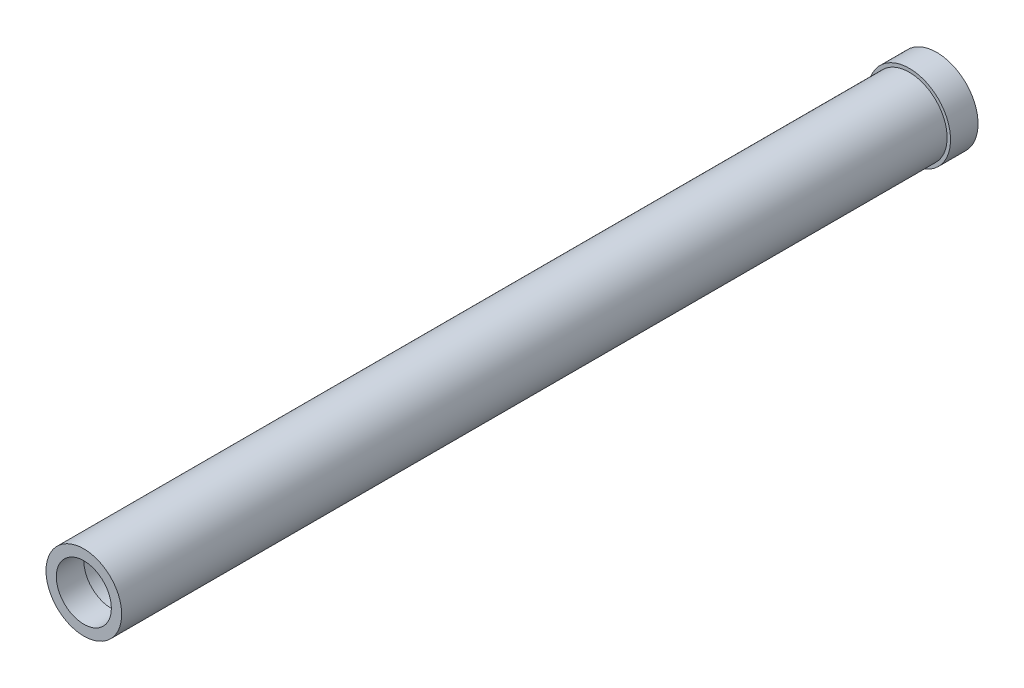
SolidWorks part; units mm, degrees
ref_plane "Front Plane" through (0, 0, 0) normal (0, 0, 1) x (1, 0, 0)
ref_plane "Top Plane" through (0, 0, 0) normal (0, 1, 0) x (1, 0, 0)
ref_plane "Right Plane" through (0, 0, 0) normal (1, 0, 0) x (0, 0, -1)
sketch "Sketch1" plane through (0, 0, 0) normal (0, 0, 1) x (1, 0, 0)
  circle A0 centre (0, 0) radius 3.4925
  circle A1 centre (0, 0) radius 2.8575
extrude "Boss-Extrude1" add sketch "Sketch1" along normal blind 76.2
sketch "Sketch2" plane through (0, 0, 76.2) normal (0, 0, 1) x (1, 0, 0)
  circle A0 centre (0, 0) radius 3.4925
  circle A1 centre (0, 0) radius 2.54
extrude "Boss-Extrude2" add sketch "Sketch2" along normal blind 2.54
sketch "Sketch3" plane through (0, 0, 0) normal (0, 0, -1) x (-1, 0, 0)
  circle A0 centre (0, 0) radius 3.81
  circle A1 centre (0, 0) radius 3.4925
extrude "Boss-Extrude3" add sketch "Sketch3" against normal blind 2.54
